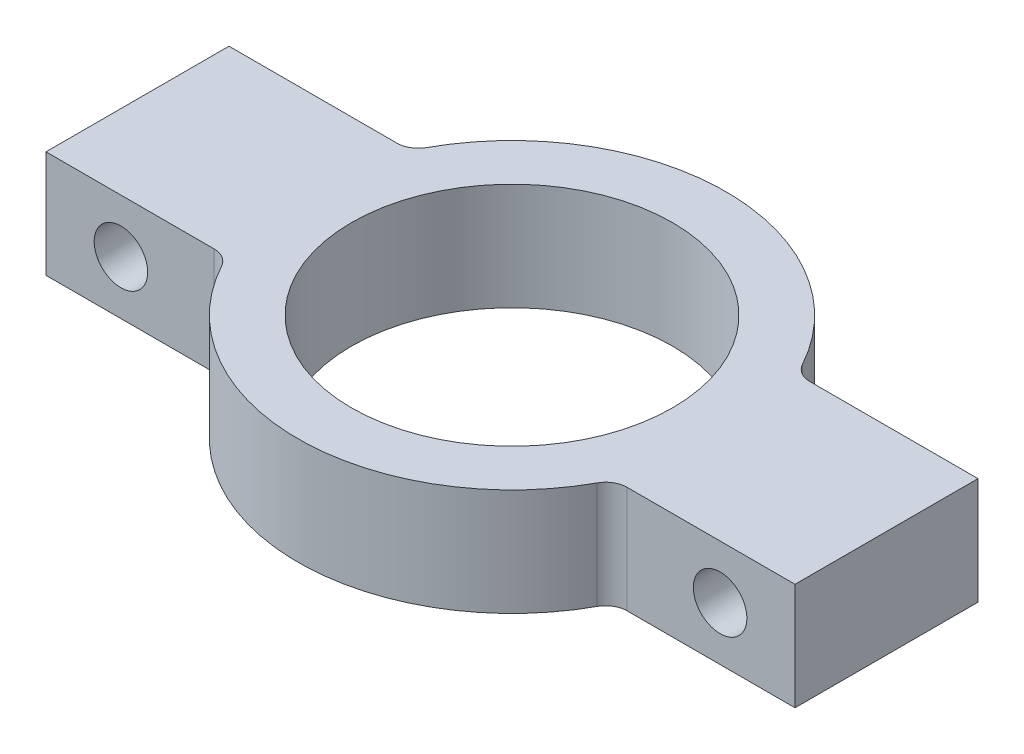
SolidWorks part; units mm, degrees
ref_plane "正面" through (0, 0, 0) normal (0, 0, 1) x (1, 0, 0)
ref_plane "平面" through (0, 0, 0) normal (0, 1, 0) x (1, 0, 0)
ref_plane "右側面" through (0, 0, 0) normal (1, 0, 0) x (0, 0, -1)
sketch "ｽｹｯﾁ1" plane through (0, 0, 0) normal (0, 1, 0) x (1, 0, 0)
  line L1 (-17.5, 4.275) -> (17.5, 4.275)
  line L2 (-17.5, 4.275) -> (-17.5, -4.275)
  line L3 (-17.5, -4.275) -> (17.5, -4.275)
  line L4 (17.5, 4.275) -> (17.5, -4.275)
  line L5 (-17.5, 4.275) -> (17.5, -4.275) construction
  line L6 (-17.5, -4.275) -> (17.5, 4.275) construction
  circle A0 centre (0, 0) radius 7.5
  circle A1 centre (0, 0) radius 10
  point P0 (0, 0)
  dimension "D3" = 15
  dimension "D1" = 8.55
  dimension "D2" = 35
  dimension "D4" = 2.5
extrude "ﾎﾞｽ - 押し出し1" add sketch "ｽｹｯﾁ1" along normal mid plane 5 contours A1 L1 L2 L3 | L1 A1 L3 A0 | L1 A1 A0 | L3 A1 L1 A0 | A1 L3 L4 L1 | L3 A1 A0
sketch "ｽｹｯﾁ2" plane through (0, 0, -4.275) normal (0, 0, -1) x (-1, 0, 0)
  line L0 (9.0402, -2.5) -> (17.5, -2.5) construction
  line L1 (17.5, -2.5) -> (17.5, 2.5) construction
  line L2 (17.5, 2.5) -> (9.0402, 2.5) construction
  line L3 (9.0402, 2.5) -> (9.0402, -2.5) construction
  line L4 (-17.5, -2.5) -> (-9.0402, -2.5) construction
  line L5 (-9.0402, -2.5) -> (-9.0402, 2.5) construction
  line L6 (-9.0402, 2.5) -> (-17.5, 2.5) construction
  line L7 (-17.5, 2.5) -> (-17.5, -2.5) construction
  line L8 (9.0402, -2.5) -> (17.5, -2.5) construction
  line L9 (17.5, -2.5) -> (17.5, 2.5) construction
  line L10 (17.5, 2.5) -> (9.0402, 2.5) construction
  line L11 (9.0402, 2.5) -> (9.0402, -2.5) construction
  line L12 (-17.5, -2.5) -> (-9.0402, -2.5) construction
  line L13 (-9.0402, -2.5) -> (-9.0402, 2.5) construction
  line L14 (-9.0402, 2.5) -> (-17.5, 2.5) construction
  line L15 (-17.5, 2.5) -> (-17.5, -2.5) construction
  line L16 (-17.5, 0) -> (17.5, 0) construction
  line L17 (0, 0) -> (0, 2.5) construction
  line L18 (9.0402, 2.5) -> (-9.0402, 2.5) construction
  circle A0 centre (14, 0) radius 1.25
  circle A1 centre (-14, 0) radius 1.25
  dimension "D1" = 2.5
  dimension "D2" = 28
extrude "ｶｯﾄ - 押し出し1" cut sketch "ｽｹｯﾁ2" against normal blind 10
fillet "ﾌｨﾚｯﾄ1" radius 1 4 edges at (-9.0402, 0, -4.275) (9.0402, 0, -4.275) (-9.0402, 0, 4.275) (9.0402, 0, 4.275)
